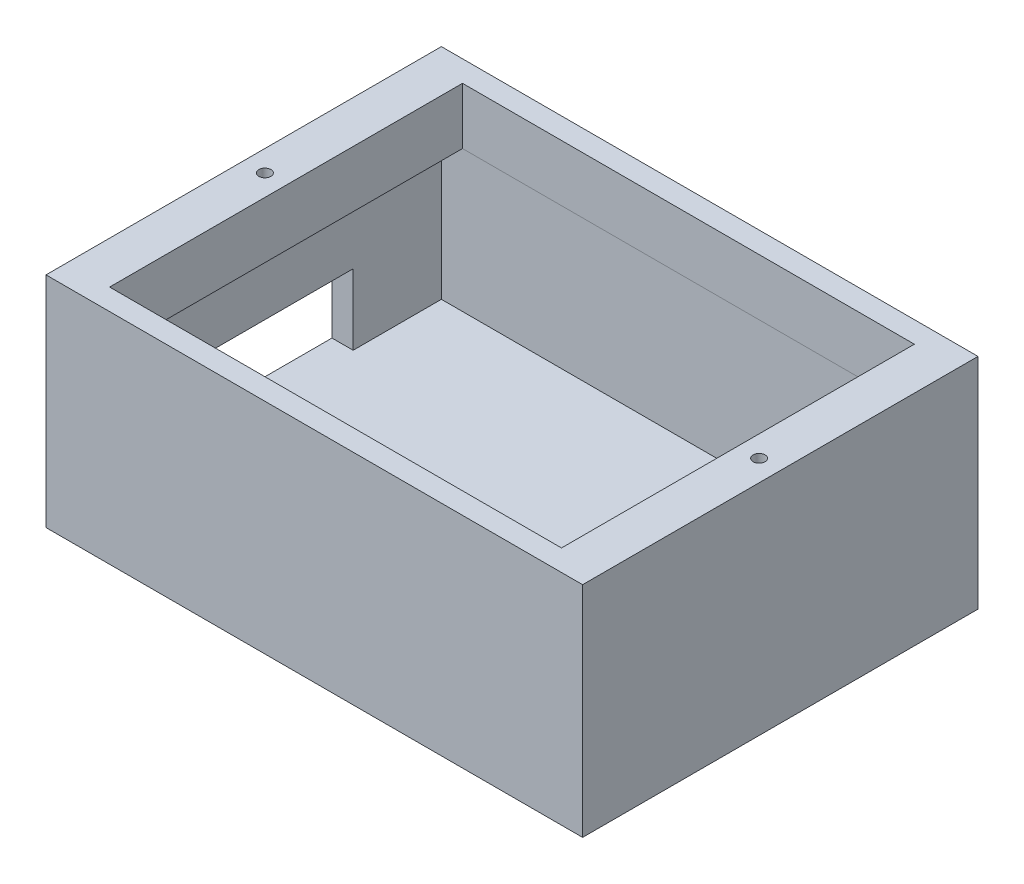
SolidWorks part; units mm, degrees
ref_plane "Front Plane" through (0, 0, 0) normal (0, 0, 1) x (1, 0, 0)
ref_plane "Top Plane" through (0, 0, 0) normal (0, 1, 0) x (1, 0, 0)
ref_plane "Right Plane" through (0, 0, 0) normal (1, 0, 0) x (0, 0, -1)
sketch "Sketch1" plane through (0, 0, 0) normal (0, 1, 0) x (1, 0, 0)
  line L1 (-38, -28) -> (38, -28)
  line L2 (-38, -28) -> (-38, 28)
  line L3 (-38, 28) -> (38, 28)
  line L4 (38, -28) -> (38, 28)
  line L5 (-38, -28) -> (38, 28) construction
  line L6 (-38, 28) -> (38, -28) construction
  point P0 (0, 0)
  dimension "D1" = 76
  dimension "D2" = 56
extrude "Boss-Extrude1" add sketch "Sketch1" along normal blind 3
sketch "Sketch2" plane through (0, 3, 0) normal (0, 1, 0) x (1, 0, 0)
  line L0 (-35, -25) -> (-35, 25)
  line L1 (-38, -28) -> (38, -28)
  line L2 (-38, -28) -> (-38, 28)
  line L3 (-38, 28) -> (38, 28)
  line L4 (38, -28) -> (38, 28)
  line L5 (-35, 25) -> (35, 25)
  line L6 (35, -25) -> (35, 25)
  line L7 (-35, -25) -> (35, -25)
  dimension "D1" = 3
extrude "Boss-Extrude2" add sketch "Sketch2" along normal blind 28
sketch "Sketch3" plane through (-38, 0, 0) normal (-1, 0, 0) x (0, 0, 1)
  line L0 (-28, 0) -> (28, 0) construction
  line L1 (-12.5, 3) -> (12.5, 3)
  line L2 (-12.5, 3) -> (-12.5, 13)
  line L3 (-12.5, 13) -> (12.5, 13)
  line L4 (12.5, 3) -> (12.5, 13)
  line L5 (-12.5, 3) -> (12.5, 13) construction
  line L6 (-12.5, 13) -> (12.5, 3) construction
  point P0 (0, 8)
  dimension "D1" = 3
  dimension "D2" = 10
  dimension "D3" = 25
extrude "Cut-Extrude1" cut sketch "Sketch3" against normal up to next
sketch "Sketch4" plane through (0, 0, 0) normal (0, 1, 0) x (1, 0, 0)
  line L0 (35, -25) -> (35, 25) construction
  line L1 (-32, -24.99) -> (32, -24.99)
  line L2 (-32, -24.99) -> (-32, 24.99)
  line L3 (-32, 24.99) -> (32, 24.99)
  line L4 (32, -24.99) -> (32, 24.99)
  line L5 (-32, -24.99) -> (32, 24.99) construction
  line L6 (-32, 24.99) -> (32, -24.99) construction
  line L7 (35, 25) -> (-35, 25) construction
  line L9 (-35, -25) -> (35, -25)
  line L10 (-35, -25) -> (-35, 25)
  line L11 (-35, 25) -> (35, 25)
  line L12 (35, -25) -> (35, 25)
  line L13 (-35, -25) -> (35, 25) construction
  line L14 (-35, 25) -> (35, -25) construction
  point P0 (0, 0)
  point P10 (0, 0)
  dimension "D1" = 3
  dimension "D2" = 0.01
extrude "Boss-Extrude3" add sketch "Sketch4" against normal blind 8 from surface at 31 starting at face at (0, 31, 0)
sketch "Sketch5" plane through (0, 31, 0) normal (0, 1, 0) x (1, 0, 0)
  line L0 (-38, 28) -> (-38, -28) construction
  line L1 (0, 0) -> (0, 15.2888) construction
  circle A0 centre (-35, 0) radius 0.85
  circle A1 centre (35, 0) radius 0.85
  point P9 (0, 0)
  dimension "D2" = 1.7
  dimension "D1" = 3
extrude "Cut-Extrude2" cut sketch "Sketch5" against normal blind 5
